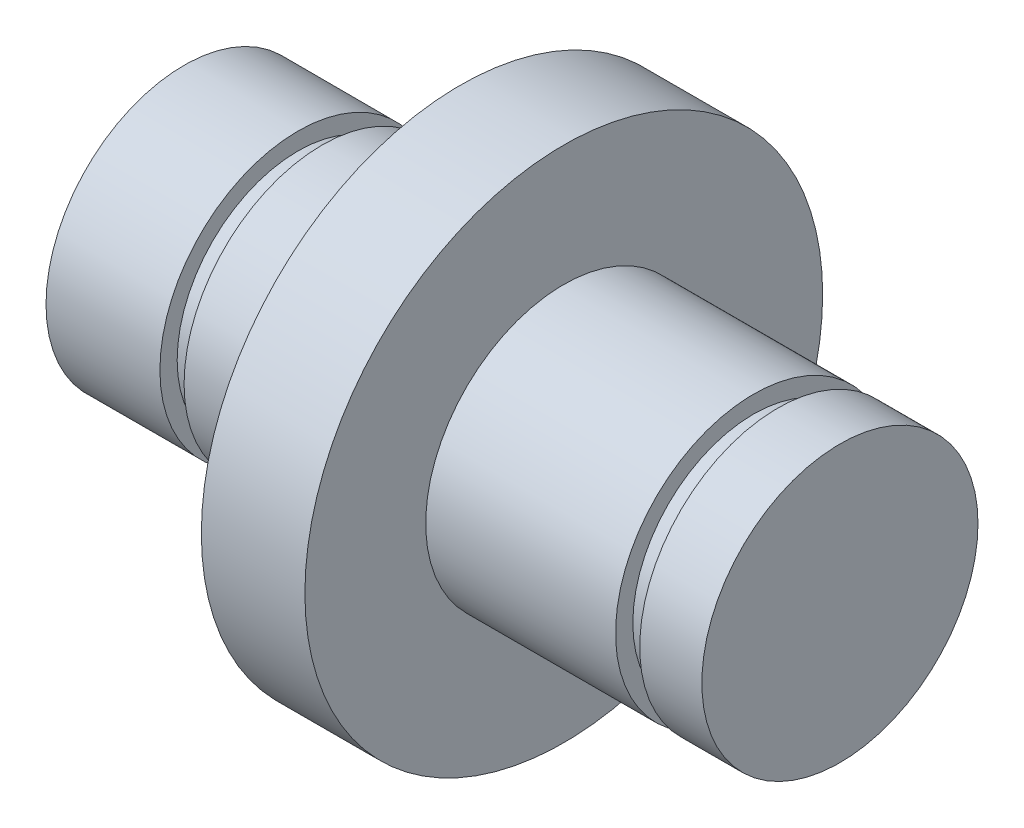
SolidWorks part; units mm, degrees
ref_plane "Piano frontale" through (0, 0, 0) normal (0, 0, 1) x (1, 0, 0)
ref_plane "Piano superiore" through (0, 0, 0) normal (0, 1, 0) x (1, 0, 0)
ref_plane "Piano destro" through (0, 0, 0) normal (1, 0, 0) x (0, 0, -1)
sketch "Schizzo1" plane through (0, 0, 0) normal (1, 0, 0) x (0, 0, -1)
  circle A0 centre (0, 0) radius 7.5
  dimension "D1" = 15
extrude "Estrusione-Estrusione1" add sketch "Schizzo1" along normal mid plane 19
sketch "Schizzo3" plane through (9.5, 0, 0) normal (1, 0, 0) x (0, 0, -1)
  circle A0 centre (0, 0) radius 4
  circle A1 centre (0, 0) radius 7.5
  circle A2 centre (0, 0) radius 7.5
  dimension "D2" = 8
  dimension "D1" = 0
extrude "Taglio-Estrusione1" cut sketch "Schizzo3" against normal blind 8
sketch "Schizzo5" plane through (-9.5, 0, 0) normal (-1, 0, 0) x (0, 0, 1)
  circle A0 centre (0, 0) radius 4
  circle A2 centre (0, 0) radius 7.5
  circle A3 centre (0, 0) radius 7.5
  dimension "D1" = 8
  dimension "D2" = 0
extrude "Taglio-Estrusione2" cut sketch "Schizzo5" against normal blind 8
sketch "Schizzo4" plane through (0, 0, 0) normal (0, 0, 1) x (1, 0, 0)
  line L0 (0, 0) -> (9.5, 0) construction
  line L1 (9.5, -4) -> (9.5, 4) construction
  line L2 (9.5, 4) -> (1.5, 4) construction
  line L3 (7.7, 4) -> (7, 4)
  line L4 (7.7, 4) -> (7.7, 3.5)
  line L5 (7.7, 3.5) -> (7, 3.5)
  line L6 (7, 4) -> (7, 3.5)
  line L7 (1.5, -7.5) -> (1.5, 7.5) construction
  line L8 (0, 0) -> (-9.5, 0) construction
  line L9 (-9.5, 4) -> (-9.5, -4) construction
  line L10 (-1.5, 4) -> (-9.5, 4) construction
  line L11 (-6.2, 4) -> (-5.5, 4)
  line L12 (-6.2, 4) -> (-6.2, 3.5)
  line L13 (-6.2, 3.5) -> (-5.5, 3.5)
  line L14 (-5.5, 4) -> (-5.5, 3.5)
  line L15 (-1.5, 7.5) -> (-1.5, -7.5) construction
  dimension "D1" = 0.7
  dimension "D2" = 3.5
  dimension "D3" = 6.2
  dimension "D4" = 0.7
  dimension "D5" = 3.5
  dimension "D6" = 4.7
revolve "Taglia-Rivoluzione1" cut sketch "Schizzo4" angle 360 about L8
